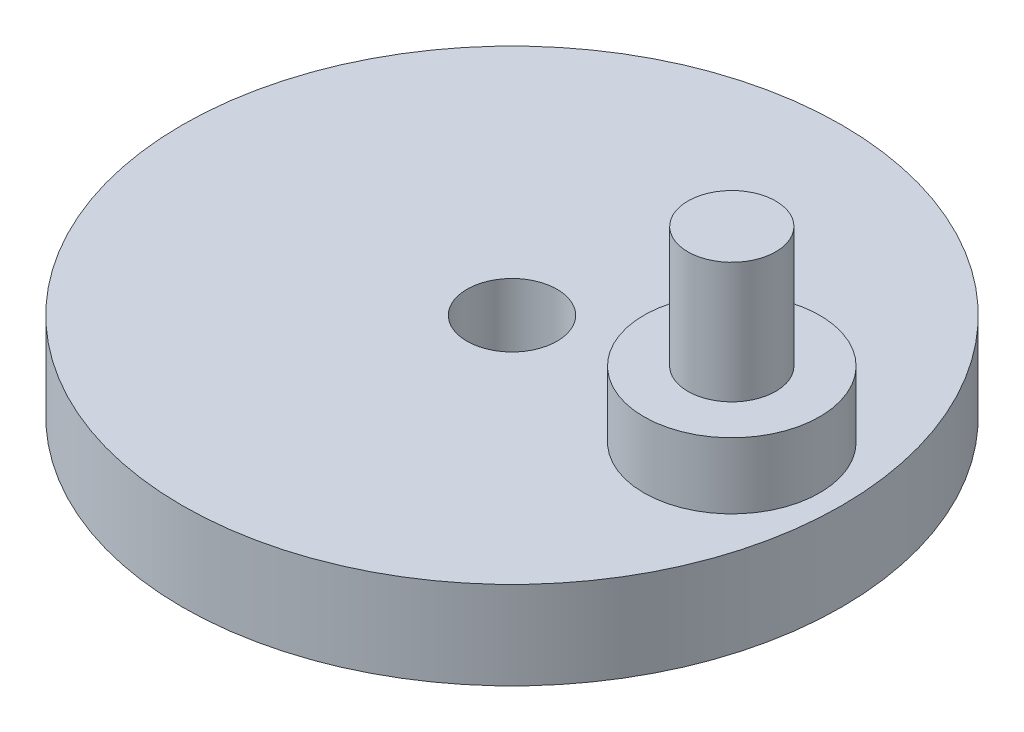
SolidWorks part; units mm, degrees
ref_plane "前视基准面" through (0, 0, 0) normal (0, 0, 1) x (1, 0, 0)
ref_plane "上视基准面" through (0, 0, 0) normal (0, 1, 0) x (1, 0, 0)
ref_plane "右视基准面" through (0, 0, 0) normal (1, 0, 0) x (0, 0, -1)
other "Configuration Table"
sketch "草图1" plane through (0, 0, 0) normal (0, 1, 0) x (1, 0, 0)
  circle A0 centre (0, 0) radius 30
  dimension "D1" = 60
extrude "凸台-拉伸1" add sketch "草图1" along normal blind 8
sketch "草图2" plane through (0, 8, 0) normal (0, 1, 0) x (1, 0, 0)
  circle A0 centre (0, 0) radius 4.1
  dimension "D1" = 8.2
extrude "切除-拉伸1" cut sketch "草图2" against normal through all contours A0
sketch "草图3" plane through (0, 8, 0) normal (0, 1, 0) x (1, 0, 0)
  circle A0 centre (20, 0) radius 8
  dimension "D1" = 16
  dimension "D2" = 20
extrude "凸台-拉伸2" add sketch "草图3" along normal blind 6 contours A0
sketch "草图4" plane through (0, 14, 0) normal (0, 1, 0) x (1, 0, 0)
  circle A0 centre (20, 0) radius 4
  circle A1 centre (20, 0) radius 8 construction
  dimension "D1" = 8
extrude "凸台-拉伸3" add sketch "草图4" along normal blind 11 contours A0
